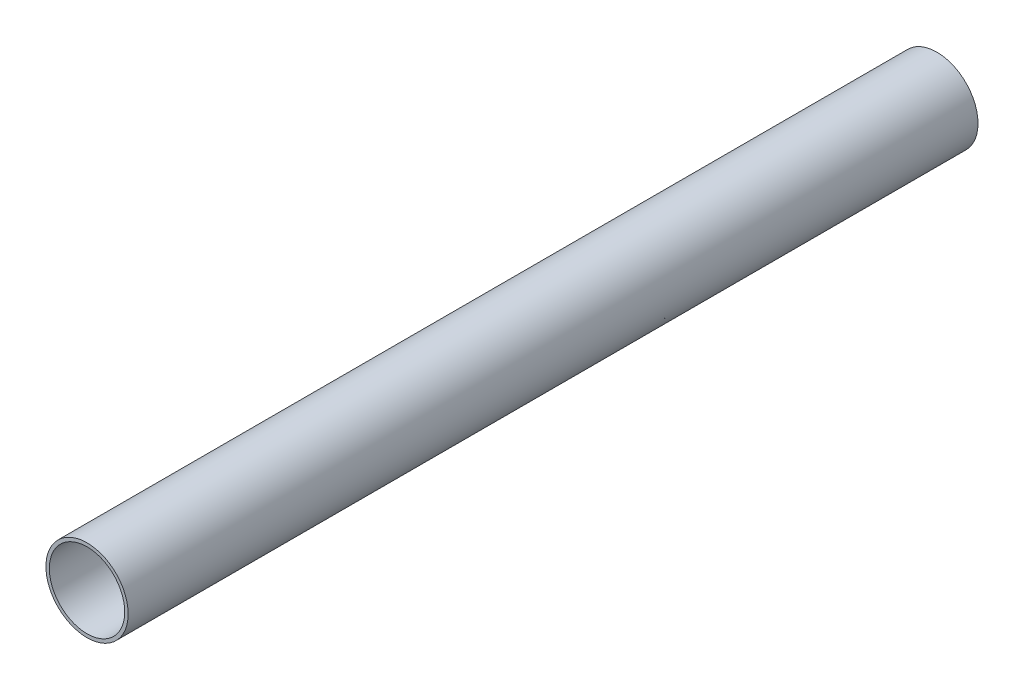
SolidWorks part; units mm, degrees
ref_plane "前视基准面" through (0, 0, 0) normal (0, 0, 1) x (1, 0, 0)
ref_plane "上视基准面" through (0, 0, 0) normal (0, 1, 0) x (1, 0, 0)
ref_plane "右视基准面" through (0, 0, 0) normal (1, 0, 0) x (0, 0, -1)
other "Configuration Table"
sketch "草图1" plane through (0, 0, 0) normal (0, 0, 1) x (1, 0, 0)
  circle A0 centre (0, 0) radius 3
  dimension "D1" = 6
extrude "凸台-拉伸1" add sketch "草图1" along normal blind 62
sketch "草图2" plane through (0, 0, 0) normal (0, 0, -1) x (-1, 0, 0)
  circle A0 centre (0, 0) radius 2.75
  dimension "D1" = 5.5
extrude "切除-拉伸1" cut sketch "草图2" against normal blind 75
